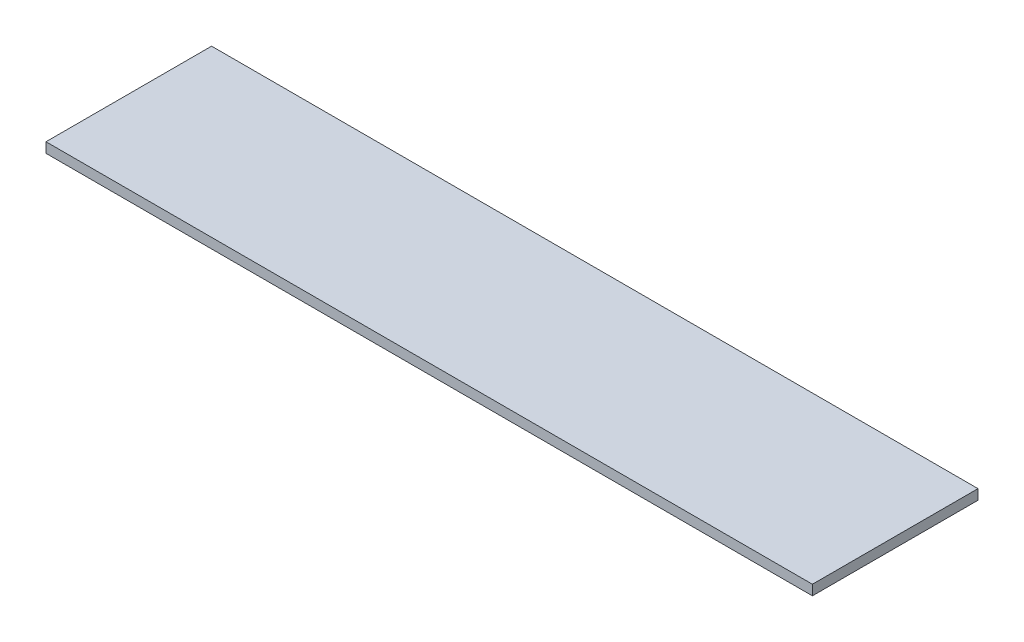
SolidWorks part; units mm, degrees
material "Acrylic (Medium-high impact)"
ref_plane "Front Plane" through (0, 0, 0) normal (0, 0, 1) x (1, 0, 0)
ref_plane "Top Plane" through (0, 0, 0) normal (0, 1, 0) x (1, 0, 0)
ref_plane "Right Plane" through (0, 0, 0) normal (1, 0, 0) x (0, 0, -1)
sketch "Sketch1" plane through (0, 0, 0) normal (0, 1, 0) x (1, 0, 0)
  line L1 (-113.1111, -1.8184) -> (80.1093, -1.8184)
  line L2 (-113.1111, -1.8184) -> (-113.1111, -43.5646)
  line L3 (-113.1111, -43.5646) -> (80.1093, -43.5646)
  line L4 (80.1093, -1.8184) -> (80.1093, -43.5646)
extrude "Extrude1" add sketch "Sketch1" along normal blind 2.54
